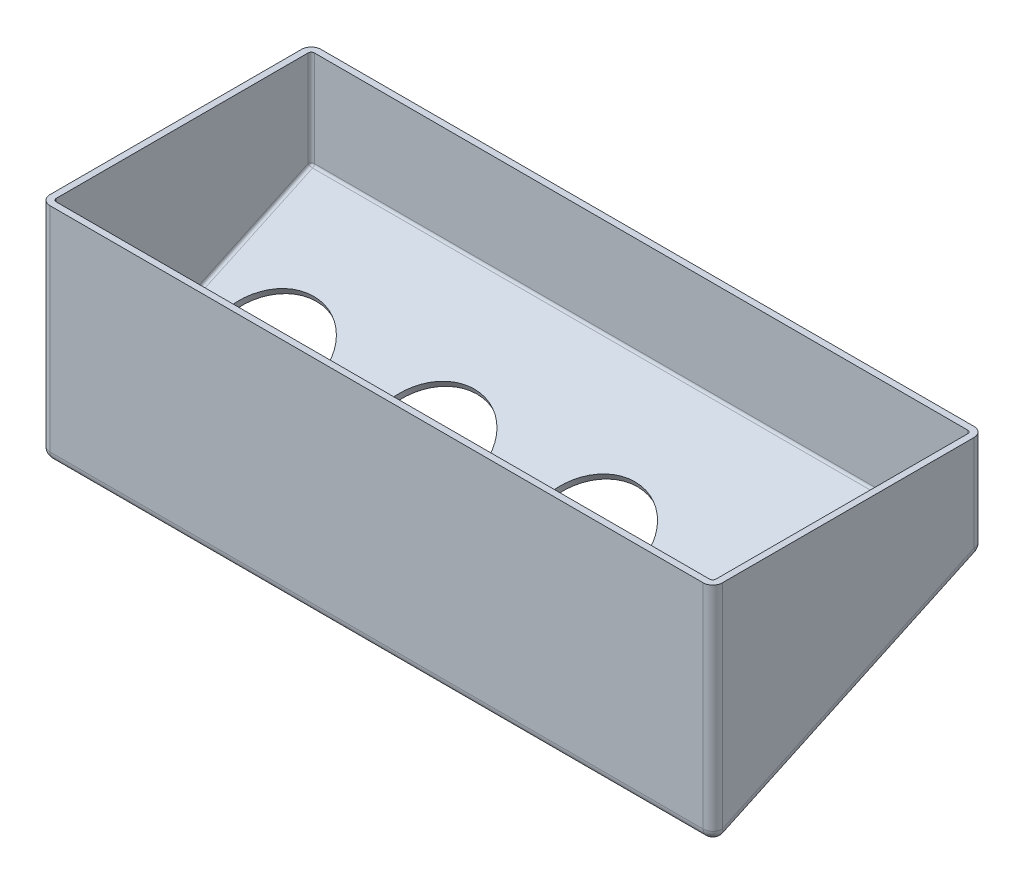
SolidWorks part; units mm, degrees
material "6061-T6 (SS)"
ref_plane "Front Plane" through (0, 0, 0) normal (0, 0, 1) x (1, 0, 0)
ref_plane "Top Plane" through (0, 0, 0) normal (0, 1, 0) x (1, 0, 0)
ref_plane "Right Plane" through (0, 0, 0) normal (1, 0, 0) x (0, 0, -1)
sketch "Sketch1" plane through (0, 0, 0) normal (1, 0, 0) x (0, 0, -1)
  line L0 (0, 0) -> (134.9502, 62.9283)
  line L1 (134.9502, 62.9283) -> (134.9502, 113.7283)
  line L2 (134.9502, 113.7283) -> (0, 113.7283)
  line L3 (0, 113.7283) -> (0, 0)
  dimension "D1" = 134.9502
  dimension "D2" = 25
  dimension "D3" = 50.8
extrude "Boss-Extrude1" add sketch "Sketch1" along normal mid plane 334.9752
sketch "Sketch2" plane through (0, 0, 0) normal (0, -0.9063, -0.4226) x (1, 0, 0)
  line L0 (-165.1, -79.0511) -> (165.1, -79.0511) construction
  line L1 (167.4876, 0) -> (167.4876, -148.9011) construction
  line L4 (0, 0) -> (0, -148.9011) construction
  line L5 (167.4876, -148.9011) -> (-167.4876, -148.9011) construction
  line L7 (35.4176, -9.2279) -> (35.4176, -96.8882) construction
  line L9 (115.4176, -15.4893) -> (115.4176, -93.6372) construction
  line L11 (-44.5824, -10.282) -> (-44.5824, -93.6401) construction
  line L13 (-124.5824, -22.474) -> (-124.5824, -89.3085) construction
  circle A0 centre (-124.5824, -79.0511) radius 25.4
  circle A1 centre (-44.5824, -79.0511) radius 25.4
  circle A2 centre (35.4176, -79.0511) radius 25.4
  circle A3 centre (115.4176, -79.0511) radius 25.4
  dimension "D5" = 50.8
  dimension "D6" = 50.8
  dimension "D7" = 50.8
  dimension "D8" = 50.8
  dimension "D1" = 80
  dimension "D2" = 80
  dimension "D3" = 80
  dimension "D4" = 52.07
  dimension "D9" = 69.85
fillet "Fillet1" radius 4.7625 8 edges at (-167.4876, 31.4642, -67.4751) (167.4876, 31.4642, -67.4751) (0, 62.9283, -134.9502) (-167.4876, 88.3283, -134.9502) (-167.4876, 56.8642, 0) (167.4876, 88.3283, -134.9502) (167.4876, 56.8642, 0) (0, 0, 0)
shell "Shell2" thickness 3.175
extrude "Cut-Extrude1" cut sketch "Sketch2" against normal blind 7.62
